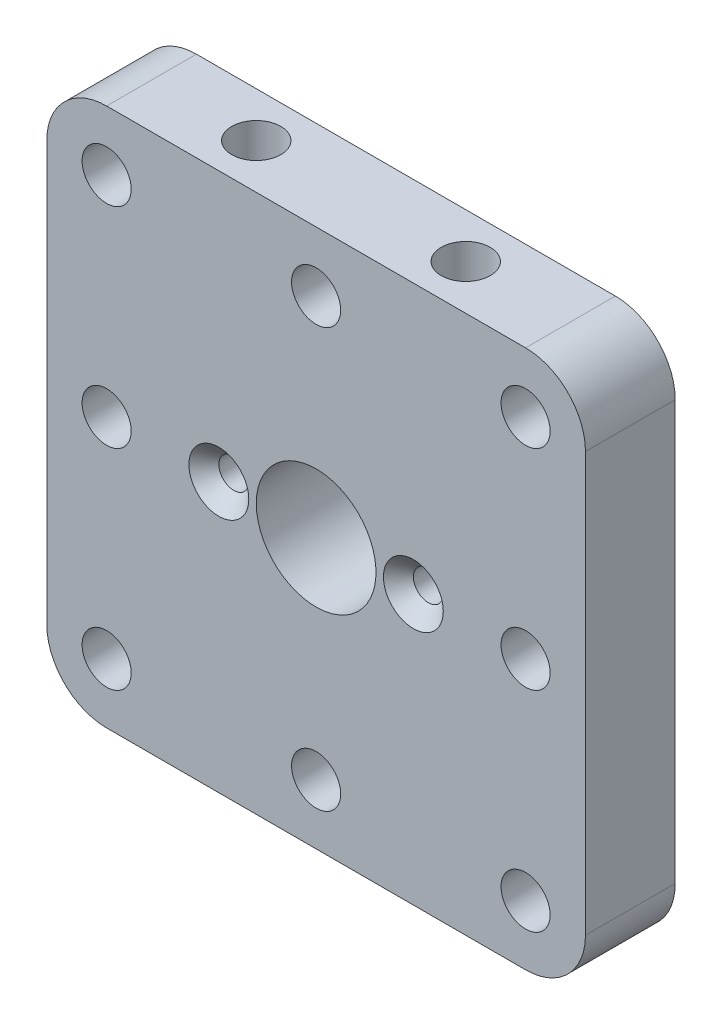
SolidWorks part; units mm, degrees
ref_plane "Front Plane" through (0, 0, 0) normal (0, 0, 1) x (1, 0, 0)
ref_plane "Top Plane" through (0, 0, 0) normal (0, 1, 0) x (1, 0, 0)
ref_plane "Right Plane" through (0, 0, 0) normal (1, 0, 0) x (0, 0, -1)
sketch "Sketch1" plane through (0, 0, 579.577) normal (0, 0, 1) x (1, 0, 0)
  line L0 (0, 762.7561) -> (28.575, 762.7561) construction
  line L1 (-28.575, 791.3311) -> (28.575, 791.3311)
  line L2 (-28.575, 791.3311) -> (-28.575, 734.1811)
  line L3 (-28.575, 734.1811) -> (28.575, 734.1811)
  line L4 (28.575, 791.3311) -> (28.575, 734.1811)
  line L5 (-28.575, 791.3311) -> (28.575, 734.1811) construction
  line L6 (-28.575, 734.1811) -> (28.575, 791.3311) construction
  line L7 (0, 762.7561) -> (0, 791.3311) construction
  line L8 (22.225, 784.9811) -> (22.225, 762.7561) construction
  circle A0 centre (-22.225, 784.9811) radius 2.6035
  circle A2 centre (0, 762.7561) radius 6.35 construction
  circle A3 centre (0, 762.7561) radius 6.35
  circle A8 centre (-10.3187, 762.7561) radius 1.5875
  circle A9 centre (10.3188, 762.7561) radius 1.5875
  circle A10 centre (22.225, 784.9811) radius 2.6035
  circle A11 centre (22.225, 762.7561) radius 2.6035
  circle A12 centre (0, 784.9811) radius 2.6035
  circle A13 centre (-22.225, 762.7561) radius 2.6035
  circle A14 centre (22.225, 740.5311) radius 2.6035
  circle A15 centre (0, 740.5311) radius 2.6035
  circle A16 centre (-22.225, 740.5311) radius 2.6035
  circle A17 centre (-10.3187, 762.7561) radius 3.1988 construction
  circle A18 centre (10.3188, 762.7561) radius 3.1988 construction
  circle A19 centre (-10.3187, 762.7561) radius 3.1988 construction
  circle A20 centre (10.3188, 762.7561) radius 3.1988 construction
  dimension "D3" = 3.175
  dimension "D5" = 5.207
  dimension "D1" = 57.15
  dimension "D2" = 57.15
  dimension "D4" = 6.35
extrude "Boss-Extrude1" add sketch "Sketch1" along normal blind 9.525
chamfer "Chamfer1" distance 1.5875 angle 45 2 edges at (11.9063, 762.7561, 589.102) (-8.7312, 762.7561, 589.102)
fillet "Fillet1" radius 6.35 4 edges at (28.575, 734.1811, 584.3395) (28.575, 791.3311, 584.3395) (-28.575, 791.3311, 584.3395) (-28.575, 734.1811, 584.3395)
sketch "Sketch2" plane through (0, 791.3311, 0) normal (0, 1, 0) x (1, 0, 0)
  line L0 (0, -579.577) -> (0, -589.102) construction
  line L1 (-22.225, -584.3395) -> (0, -584.3395) construction
  line L4 (-22.225, -589.102) -> (22.225, -589.102)
  line L5 (22.225, -589.102) -> (22.225, -579.577)
  line L6 (22.225, -579.577) -> (-22.225, -579.577)
  line L7 (-22.225, -579.577) -> (-22.225, -589.102)
  line L8 (-22.225, -589.102) -> (22.225, -589.102) construction
  line L9 (22.225, -589.102) -> (22.225, -579.577) construction
  line L10 (22.225, -579.577) -> (-22.225, -579.577) construction
  line L11 (-22.225, -579.577) -> (-22.225, -589.102) construction
  circle A0 centre (-11.1125, -584.3395) radius 2.6035
  circle A1 centre (11.1125, -584.3395) radius 2.6035
  dimension "D2" = 5.207
  dimension "D1" = 0
extrude "Cut-Extrude1" cut sketch "Sketch2" against normal blind 12.7
